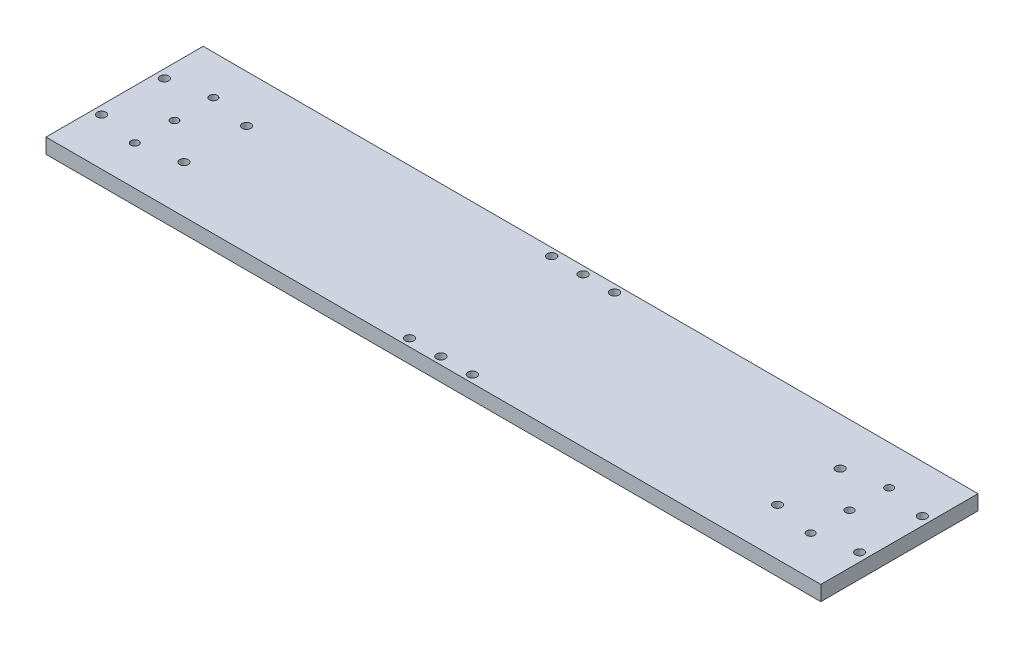
SolidWorks part; units mm, degrees
ref_plane "Plano frontal" through (0, 0, 0) normal (0, 0, 1) x (1, 0, 0)
ref_plane "Plano superior" through (0, 0, 0) normal (0, 1, 0) x (1, 0, 0)
ref_plane "Plano direito" through (0, 0, 0) normal (1, 0, 0) x (0, 0, -1)
sketch "Esboço3" plane through (0, 0, 0) normal (0, 1, 0) x (1, 0, 0)
  line L0 (-246.505, 50) -> (246.505, -50) construction
  line L1 (-246.505, -50) -> (246.505, -50)
  line L2 (-246.505, -50) -> (-246.505, 50)
  line L3 (-246.505, 50) -> (246.505, 50)
  line L4 (246.505, -50) -> (246.505, 50)
  line L5 (-183.495, 50) -> (-183.495, -50)
  line L6 (183.495, 50) -> (183.495, -50)
  dimension "D1" = 493.01
  dimension "D2" = 100
  dimension "D3" = 63.01
  dimension "D4" = 63.01
extrude "Ressalto-extrusão1" add sketch "Esboço3" against normal blind 9.525 contours L0 L2 L1 L5 | L5 L0 L6 L3 | L0 L5 L1 L6 | L0 L6 L1 | L6 L0 L4 L3 | L3 L0 L5
sketch "Esboço5" plane through (0, 0, 0) normal (0, 1, 0) x (1, 0, 0)
  line L0 (0, -50) -> (0, 50) construction
  line L1 (-246.505, -50) -> (246.505, -50) construction
  line L2 (-246.505, 50) -> (246.505, 50) construction
  line L3 (-246.505, -40.475) -> (246.505, -40.475) construction
  line L4 (-246.505, -50) -> (-246.505, 50) construction
  line L5 (246.505, -50) -> (246.505, 50) construction
  line L6 (-246.505, 40.475) -> (246.505, 40.475) construction
  line L7 (-79.6616, 0) -> (77.24, 0) construction
  circle A0 centre (0, -45.235) radius 2.78
  circle A1 centre (-20, -45.235) radius 2.78
  circle A2 centre (20, -45.235) radius 2.78
  circle A3 centre (-20, 45.235) radius 2.78
  circle A4 centre (20, 45.235) radius 2.78
  circle A5 centre (0, 45.235) radius 2.78
  dimension "D3" = 5.56
  dimension "D7" = 5.56
  dimension "D8" = 5.56
  dimension "D1" = 9.525
  dimension "D2" = 9.525
  dimension "D4" = 4.76
  dimension "D5" = 20
  dimension "D6" = 20
extrude "Corte-extrusão2" cut sketch "Esboço5" against normal blind 10
sketch "Esboço8" plane through (0, -9.525, 0) normal (0, -1, 0) x (1, 0, 0)
  line L0 (0, 50) -> (0, -50) construction
  line L1 (-246.505, 50) -> (246.505, 50) construction
  line L2 (-246.505, -50) -> (246.505, -50) construction
  line L3 (-241.16, 19.9509) -> (-188.84, 19.9509) construction
  line L4 (-188.84, 19.9509) -> (-188.84, -19.95) construction
  line L5 (-188.84, -19.95) -> (-241.16, -19.95) construction
  line L6 (-241.16, -19.95) -> (-241.16, 19.9509) construction
  line L7 (-241.16, 19.9509) -> (-188.84, -19.95) construction
  circle A0 centre (-188.84, 19.9509) radius 2.75
  circle A1 centre (-188.84, -19.95) radius 2.75
  circle A2 centre (-241.16, 19.9509) radius 2.75
  circle A3 centre (-241.16, -19.95) radius 2.75
  circle A4 centre (241.16, -19.95) radius 2.75
  circle A5 centre (241.16, 19.9509) radius 2.75
  circle A6 centre (188.84, -19.95) radius 2.75
  circle A7 centre (188.84, 19.9509) radius 2.75
  dimension "D2" = 5.5
  dimension "D3" = 5.5
  dimension "D4" = 5.5
  dimension "D5" = 5.5
  dimension "D1" = 5.345
extrude "Corte-extrusão4" cut sketch "Esboço8" against normal blind 10
sketch "Esboço9" plane through (0, -9.525, 0) normal (0, -1, 0) x (1, 0, 0)
  line L0 (0, 0) -> (0, -25) construction
  circle A0 centre (215, 25) radius 5
  circle A1 centre (215, 0) radius 5
  circle A2 centre (215, -25) radius 5
  circle A3 centre (-215, -25) radius 5
  circle A4 centre (-215, 0) radius 5
  circle A5 centre (-215, 25) radius 5
  dimension "D1" = 10
  dimension "D2" = 10
  dimension "D3" = 10
  dimension "D4" = 25
  dimension "D5" = 25
  dimension "D6" = 25
  dimension "D7" = 31.505
extrude "Corte-extrusão5" cut sketch "Esboço9" against normal blind 0.7
sketch "Esboço10" plane through (0, -8.825, 0) normal (0, -1, 0) x (1, 0, 0)
  line L0 (0, 0) -> (0, -30) construction
  circle A0 centre (215, 25) radius 5
  circle A1 centre (214.7625, 0) radius 5
  circle A2 centre (215, -25) radius 5
  circle A3 centre (-215, -25) radius 5
  circle A4 centre (-214.7625, 0) radius 5
  circle A5 centre (-215, 25) radius 5
extrude "Corte-extrusão6" cut sketch "Esboço10" against normal blind 2.5 draft 45
sketch "Esboço11" plane through (0, -9.525, 0) normal (0, -1, 0) x (1, 0, 0)
  line L0 (0, 0) -> (0, 78.9568) construction
  circle A0 centre (215, 25) radius 2.5
  circle A1 centre (214.7625, 0) radius 2.5
  circle A2 centre (215, -25) radius 2.5
  circle A3 centre (-215, -25) radius 2.5
  circle A4 centre (-214.7625, 0) radius 2.5
  circle A5 centre (-215, 25) radius 2.5
  dimension "D1" = 5
  dimension "D2" = 5
  dimension "D3" = 5
extrude "Corte-extrusão7" cut sketch "Esboço11" against normal blind 10
